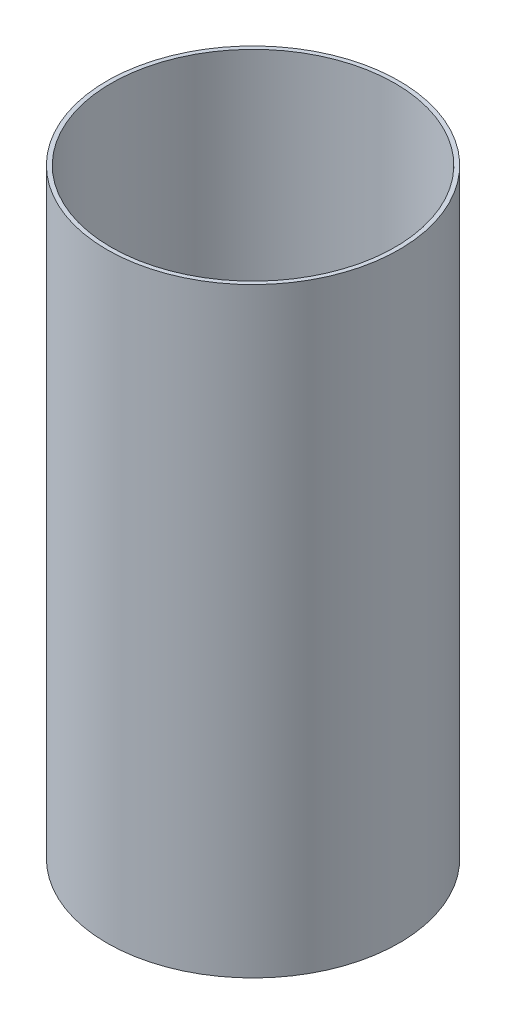
SolidWorks part; units mm, degrees
material "7075-T6 (SN)"
ref_plane "Front Plane" through (0, 0, 0) normal (0, 0, 1) x (1, 0, 0)
ref_plane "Top Plane" through (0, 0, 0) normal (0, 1, 0) x (1, 0, 0)
ref_plane "Right Plane" through (0, 0, 0) normal (1, 0, 0) x (0, 0, -1)
sketch "Sketch1" plane through (0, 0, 0) normal (0, 1, 0) x (1, 0, 0)
  circle A0 centre (0, 0) radius 49.4538
  circle A1 centre (0, 0) radius 48.0441
  dimension "D1" = 98.9076
  dimension "D2" = 96.0882
extrude "Boss-Extrude1" add sketch "Sketch1" along normal mid plane 203.2
equation "\"CF_OD_A\"= 4.015in"
equation "\"CF_ID_A\"= 3.904in"
equation "\"KF_ID_A\"= 4.015in ' Kevlar airframe ID"
equation "\"CF_OD_C\"= 3.894in ' VERIFY Coupler OD"
equation "\"CF_ID_C\"= 3.783in ' VERIFY Coupler ID"
equation "\"KF_WALL\"= 0.0625in"
equation "\"AF_01\"=10in"
equation "\"AF_02\"=22in"
equation "\"AF_03\"=56in"
equation "\"B_CF_OD\"=6.17in"
equation "\"B_CF_ID\"=6in"
equation "\"B_CF_WT\"=0.085in"
equation "\"B_Fin_Root\"=18in"
equation "\"Al_WALL\"=0.1in"
equation "\"AL_ID_A\"=3.9in"
equation "\"D1@Sketch1\"=\"CF_OD_C\""
equation "\"D2@Sketch1\"=\"CF_ID_C\""
